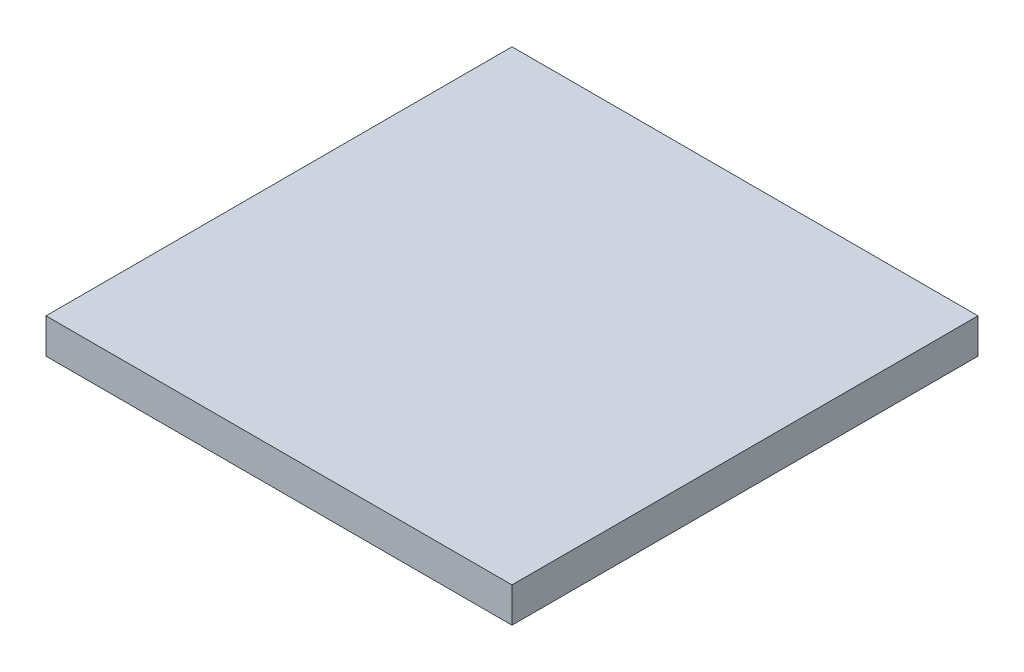
SolidWorks part; units mm, degrees
ref_plane "前视基准面" through (0, 0, 0) normal (0, 0, 1) x (1, 0, 0)
ref_plane "上视基准面" through (0, 0, 0) normal (0, 1, 0) x (1, 0, 0)
ref_plane "右视基准面" through (0, 0, 0) normal (1, 0, 0) x (0, 0, -1)
sketch "草图1" plane through (0, 0, 0) normal (0, 1, 0) x (1, 0, 0)
  circle A0 centre (0, 0) radius 8
  dimension "D1" = 16
extrude "凸台-拉伸1" add sketch "草图1" along normal blind 2
sketch "草图2" plane through (0, 2, 0) normal (0, 1, 0) x (1, 0, 0)
  circle A0 centre (0, 0) radius 2
  dimension "D1" = 4
extrude "凸台-拉伸2" add sketch "草图2" along normal blind 5
sketch "草图3" plane through (0, 7, 0) normal (0, 1, 0) x (1, 0, 0)
  line L1 (-20, 20) -> (20, 20)
  line L2 (-20, 20) -> (-20, -20)
  line L3 (-20, -20) -> (20, -20)
  line L4 (20, 20) -> (20, -20)
  line L5 (-20, 20) -> (20, -20) construction
  line L6 (-20, -20) -> (20, 20) construction
  point P0 (0, 0)
  dimension "D1" = 40
  dimension "D2" = 40
extrude "凸台-拉伸3" add sketch "草图3" along normal blind 3
